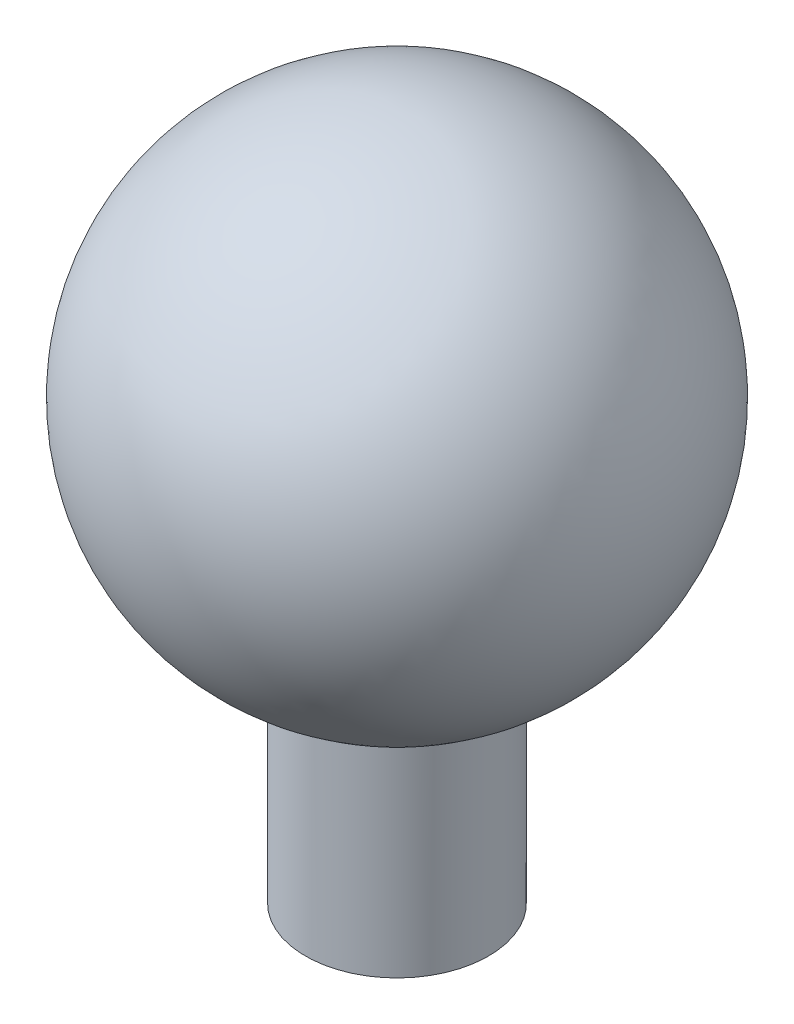
SolidWorks part; units mm, degrees
ref_plane "Front Plane" through (0, 0, 0) normal (0, 0, 1) x (1, 0, 0)
ref_plane "Top Plane" through (0, 0, 0) normal (0, 1, 0) x (1, 0, 0)
ref_plane "Right Plane" through (0, 0, 0) normal (1, 0, 0) x (0, 0, -1)
sketch "Sketch1" plane through (0, 0, 0) normal (0, 0, 1) x (1, 0, 0)
  line L0 (0, 0) -> (-12, 0)
  line L1 (-12, 0) -> (-12, 27.2965)
  line L16 (0, 0) -> (0, 90)
  arc A0 (0, 90) -> (-12, 27.2965) centre (0, 57.5) ccw
  dimension "D1" = 65
  dimension "D2" = 90
  dimension "D3" = 12
revolve "Revolve1" add sketch "Sketch1" angle 360 about L16
sketch "Sketch2" plane through (0, 0, 0) normal (0, -1, 0) x (-1, 0, 0)
  circle A0 centre (0, 0) radius 5
  circle A1 centre (0, -22) radius 5
  circle A2 centre (0, 22) radius 5
  dimension "D1" = 10
  dimension "D3" = 10
  dimension "D4" = 10
  dimension "D2" = 22
  dimension "D5" = 22
extrude "Cut-Extrude1" cut sketch "Sketch2" against normal blind 30 contours A0
